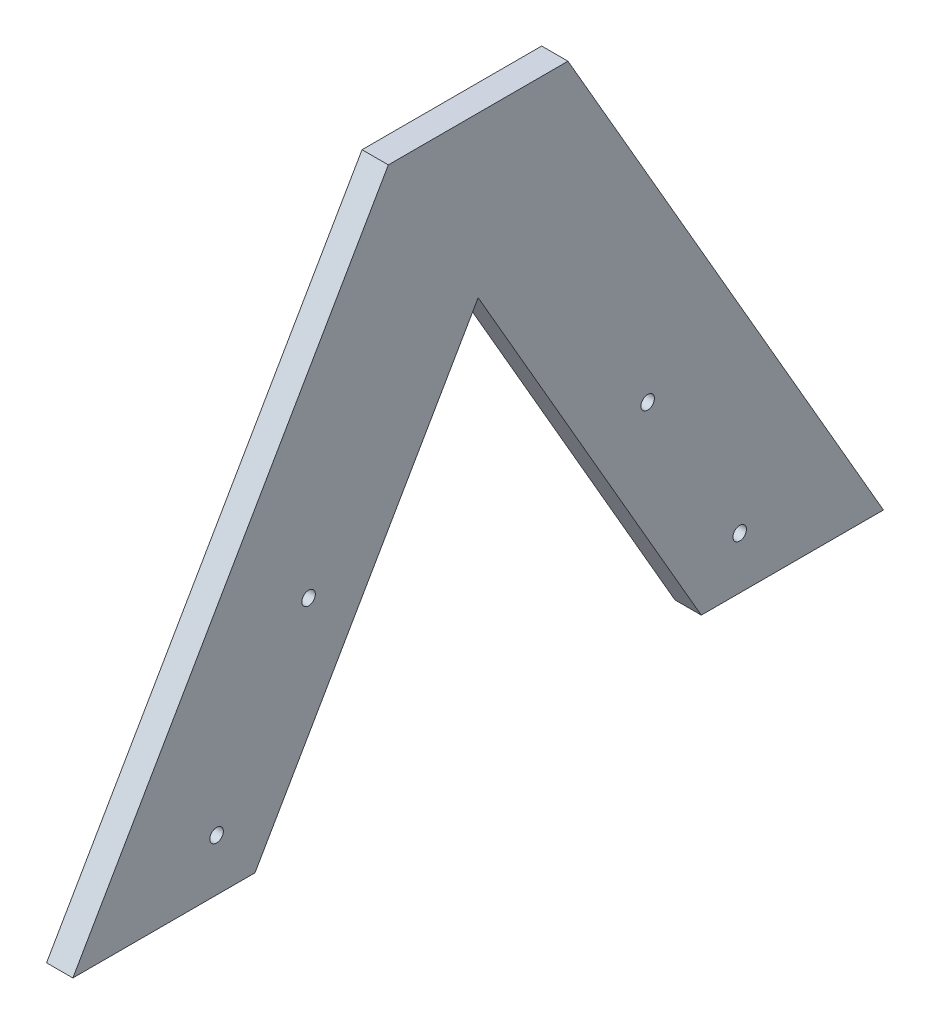
SolidWorks part; units mm, degrees
ref_plane "Front Plane" through (0, 0, 0) normal (0, 0, 1) x (1, 0, 0)
ref_plane "Top Plane" through (0, 0, 0) normal (0, 1, 0) x (1, 0, 0)
ref_plane "Right Plane" through (0, 0, 0) normal (1, 0, 0) x (0, 0, -1)
sketch "Sketch1" plane through (0, 0, 0) normal (1, 0, 0) x (0, 0, -1)
  line L0 (0, 0) -> (76.2, 131.9823)
  line L1 (119.5861, 131.9823) -> (195.7861, 0)
  line L2 (0, 0) -> (43.9941, 0)
  line L3 (43.9941, 0) -> (97.893, 93.3557)
  line L4 (97.893, 93.3557) -> (151.792, 0)
  line L5 (151.792, 0) -> (195.7861, 0)
  line L6 (76.2, 131.9823) -> (119.5861, 131.9823)
  dimension "D1" = 152.4
  dimension "D2" = 152.4
  dimension "D3" = 38.1
  dimension "D4" = 38.1
  dimension "D5" = 60
extrude "Boss-Extrude1" add sketch "Sketch1" along normal blind 6.35
hole_wizard "CSK for #4 Flat Head Machine Screw1" positions "Sketch3" profile "Sketch2" countersink size "#4" standard "ANSI Inch" end condition through all
sketch "Sketch3" plane through (0, 0, 0) normal (-1, 0, 0) x (0, 0, 1)
  point P0 (-161.0664, 12.5113)
  point P3 (-138.8414, 51.0061)
  point P6 (-56.9447, 51.0061)
  point P9 (-34.7197, 12.5113)
sketch "Sketch2" plane through (0, 12.5113, -161.0664) normal (0, 1, 0) x (0, 0, 1)
  line L0 (0, 0) -> (0, 6.35)
  line L1 (0, 6.35) -> (1.6319, 6.35)
  line L2 (1.6319, 6.35) -> (1.6319, 1.4098)
  line L3 (1.6319, 1.4098) -> (2.8575, 0)
  line L5 (2.8575, 0) -> (0, 0)
  line L6 (-1.6319, 1.4098) -> (-2.8575, 0) construction
  line L11 (0, -6.35) -> (0, 107.95) construction
  dimension "Thru Hole Dia." = 3.2639
  dimension "Thru Hole Depth" = 6.35
  dimension "Near C'Sink Dia." = 5.715
  dimension "Near C'Sink Angle" = 82
